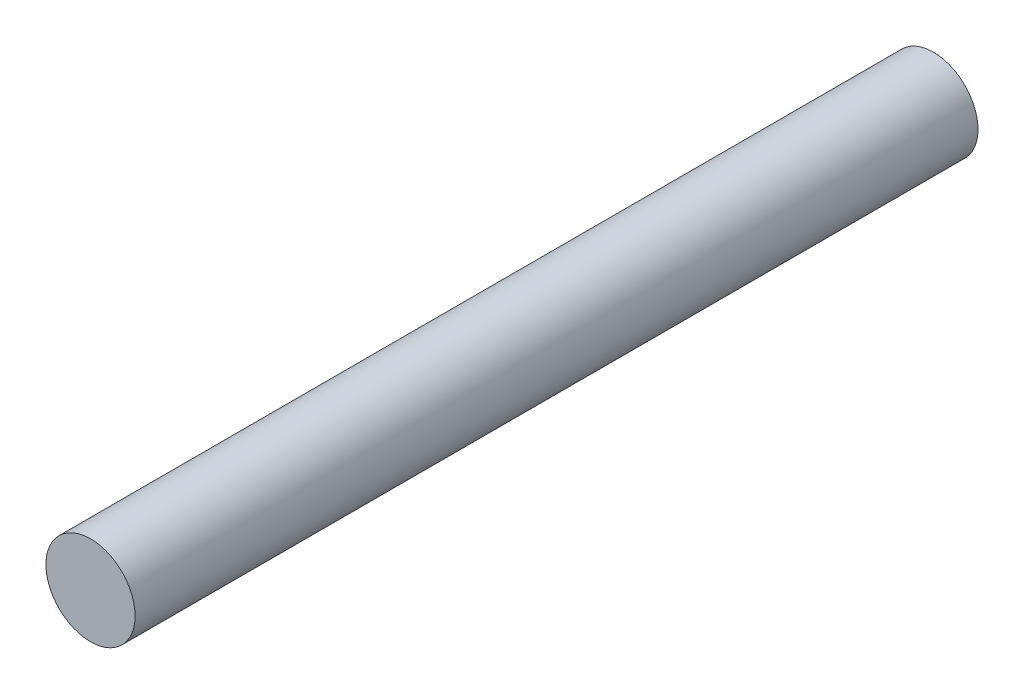
SolidWorks part; units mm, degrees
ref_plane "Front Plane" through (0, 0, 0) normal (0, 0, 1) x (1, 0, 0)
ref_plane "Top Plane" through (0, 0, 0) normal (0, 1, 0) x (1, 0, 0)
ref_plane "Right Plane" through (0, 0, 0) normal (1, 0, 0) x (0, 0, -1)
sketch "Sketch1" plane through (0, 0, 0) normal (0, 0, 1) x (1, 0, 0)
  circle A0 centre (0, 0) radius 6.35
  dimension "D1" = 12.7
extrude "Boss-Extrude1" add sketch "Sketch1" against normal blind 120
